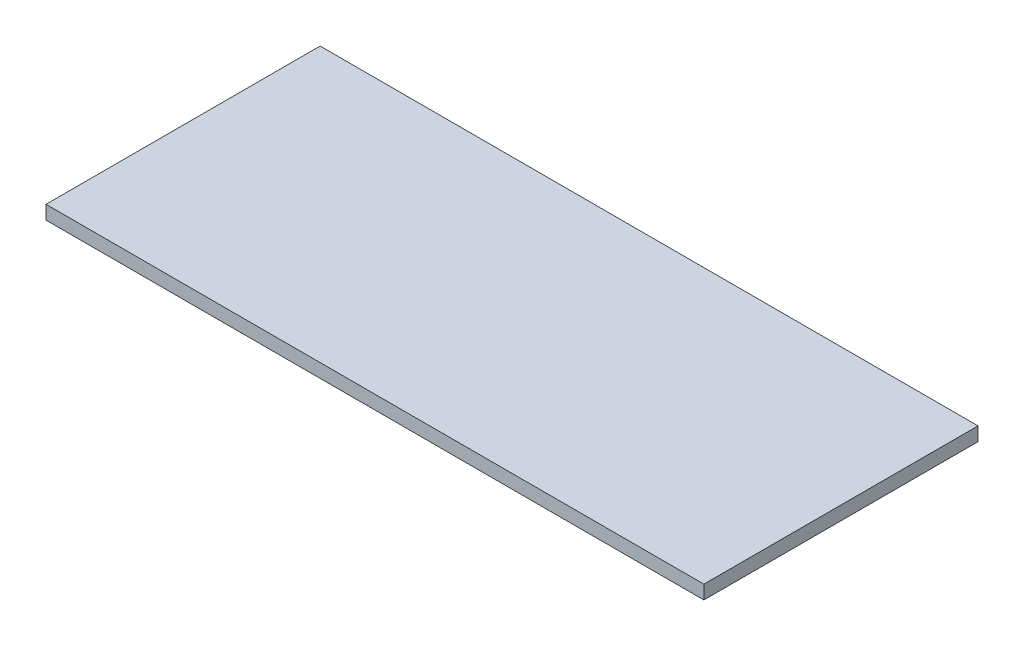
SolidWorks part; units mm, degrees
ref_plane "Front Plane" through (0, 0, 0) normal (0, 0, 1) x (1, 0, 0)
ref_plane "Top Plane" through (0, 0, 0) normal (0, 1, 0) x (1, 0, 0)
ref_plane "Right Plane" through (0, 0, 0) normal (1, 0, 0) x (0, 0, -1)
sketch "Sketch1" plane through (0, 0, 0) normal (0, 1, 0) x (1, 0, 0)
  line L1 (-80.5584, 34.1359) -> (1119.4416, 34.1359)
  line L2 (-80.5584, 34.1359) -> (-80.5584, -465.8641)
  line L3 (-80.5584, -465.8641) -> (1119.4416, -465.8641)
  line L4 (1119.4416, 34.1359) -> (1119.4416, -465.8641)
  dimension "D1" = 1200
  dimension "D2" = 500
extrude "Boss-Extrude1" add sketch "Sketch1" along normal blind 25 contours L1 L4 L3 L2
